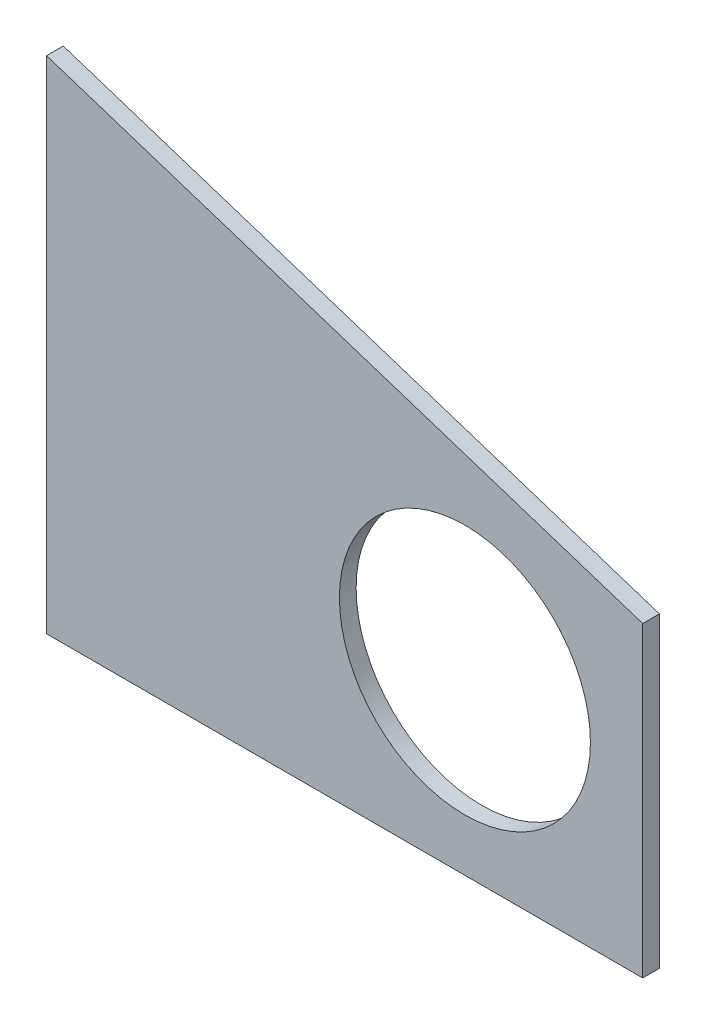
SolidWorks part; units mm, degrees
ref_plane "前视基准面" through (0, 0, 0) normal (0, 0, 1) x (1, 0, 0)
ref_plane "上视基准面" through (0, 0, 0) normal (0, 1, 0) x (1, 0, 0)
ref_plane "右视基准面" through (0, 0, 0) normal (1, 0, 0) x (0, 0, -1)
other "Configuration Table"
sketch "草图1" plane through (0, 0, 0) normal (0, 0, 1) x (1, 0, 0)
  line L0 (0, 0) -> (0, 239.3582)
  line L1 (0, 239.3582) -> (285, 146.7561)
  line L2 (285, 146.7561) -> (285, 0)
  line L3 (285, 0) -> (0, 0)
  circle A0 centre (200, 85) radius 85 construction
  circle A1 centre (200, 85) radius 60
  dimension "D1" = 170
  dimension "D4" = 120
  dimension "D2" = 200
  dimension "D3" = 72
extrude "凸台-拉伸1" add sketch "草图1" along normal blind 8
